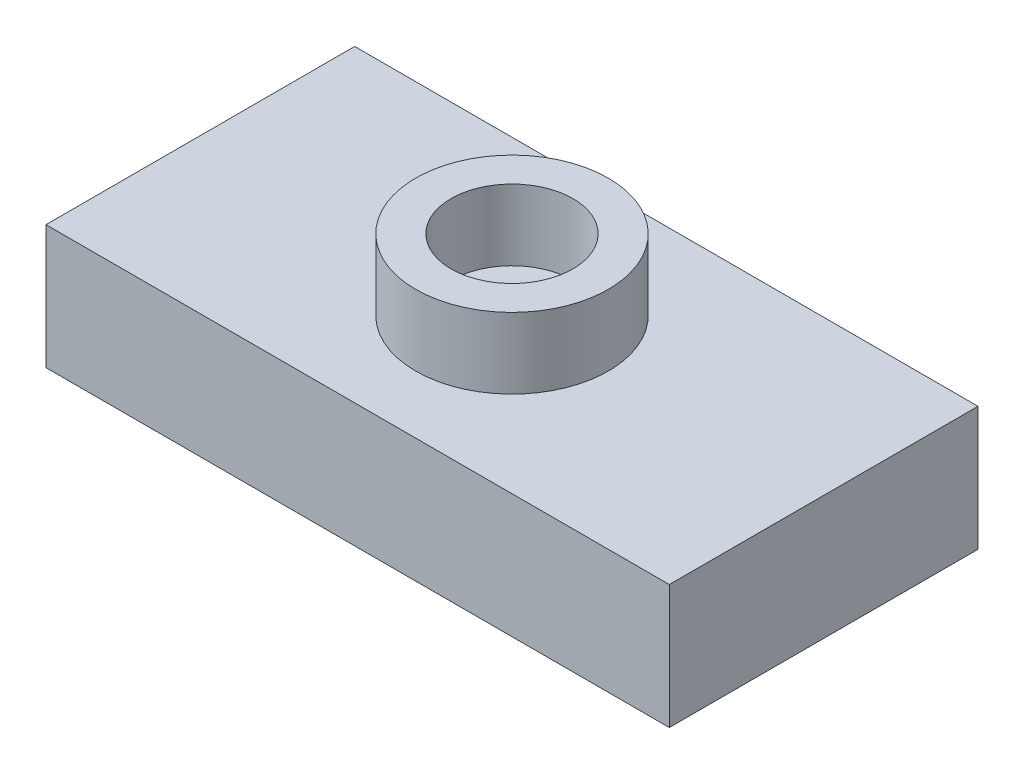
SolidWorks part; units mm, degrees
ref_plane "Front Plane" through (0, 0, 0) normal (0, 0, 1) x (1, 0, 0)
ref_plane "Top Plane" through (0, 0, 0) normal (0, 1, 0) x (1, 0, 0)
ref_plane "Right Plane" through (0, 0, 0) normal (1, 0, 0) x (0, 0, -1)
sketch "Sketch1" plane through (0, 0, 0) normal (0, 1, 0) x (1, 0, 0)
  line L1 (-7.925, 3.925) -> (7.925, 3.925)
  line L2 (-7.925, 3.925) -> (-7.925, -3.925)
  line L3 (-7.925, -3.925) -> (7.925, -3.925)
  line L4 (7.925, 3.925) -> (7.925, -3.925)
  line L5 (-7.925, 3.925) -> (7.925, -3.925) construction
  line L6 (-7.925, -3.925) -> (7.925, 3.925) construction
  point P0 (0, 0)
  dimension "D1" = 15.85
  dimension "D2" = 7.85
extrude "Boss-Extrude1" add sketch "Sketch1" against normal blind 3.15
shell "Shell1" thickness 1.5
sketch "Sketch2" plane through (0, 0, 0) normal (0, 1, 0) x (1, 0, 0)
  circle A0 centre (0, 0) radius 2.45
  circle A1 centre (0, 0) radius 1.55
  dimension "D1" = 4.9
  dimension "D2" = 3.1
extrude "Boss-Extrude2" add sketch "Sketch2" along normal blind 1.8
